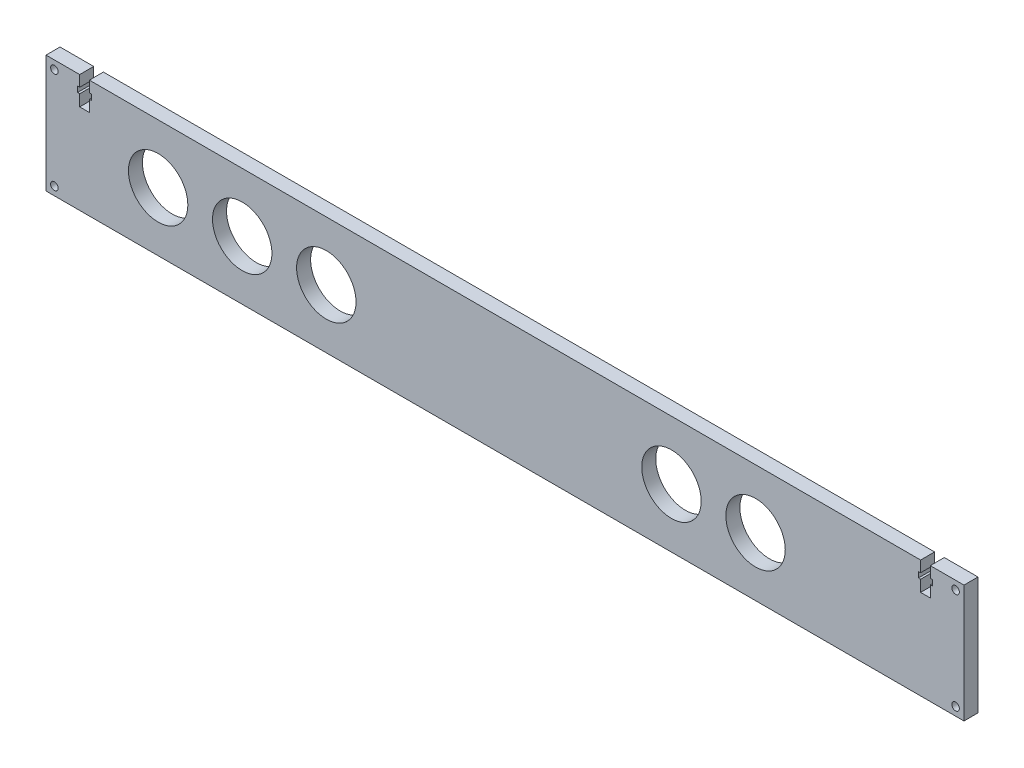
SolidWorks part; units mm, degrees
material "Acrylic (Medium-high impact)"
ref_plane "Front Plane" through (0, 0, 0) normal (0, 0, 1) x (1, 0, 0)
ref_plane "Top Plane" through (0, 0, 0) normal (0, 1, 0) x (1, 0, 0)
ref_plane "Right Plane" through (0, 0, 0) normal (1, 0, 0) x (0, 0, -1)
sketch "Sketch1" plane through (0, 0, 0) normal (0, 0, 1) x (1, 0, 0)
  line L1 (-458.8532, 202.2287) -> (-42.9282, 202.2287)
  line L2 (-458.8532, 202.2287) -> (-458.8532, 148.8887)
  line L3 (-458.8532, 148.8887) -> (-42.9282, 148.8887)
  line L4 (-42.9282, 202.2287) -> (-42.9282, 148.8887)
  line L5 (-458.8532, 202.2287) -> (-42.9282, 148.8887) construction
  line L6 (-458.8532, 148.8887) -> (-42.9282, 202.2287) construction
  point P0 (-250.8907, 175.5587)
  dimension "D1" = 415.925
  dimension "D2" = 53.34
extrude "Boss-Extrude1" add sketch "Sketch1" along normal blind 6.35
sketch "Sketch6" plane through (0, 0, 6.35) normal (0, 0, 1) x (1, 0, 0)
  line L0 (-42.9282, 175.5587) -> (-460.2982, 175.5587) construction
  line L1 (-42.9282, 148.8887) -> (-42.9282, 202.2287) construction
  line L2 (-458.8532, 202.2287) -> (-458.8532, 148.8887) construction
  circle A0 centre (-408.0532, 175.5587) radius 13.462
  circle A1 centre (-175.4677, 175.5587) radius 13.462
  circle A2 centre (-369.9532, 175.5587) radius 13.462
  circle A3 centre (-331.8532, 175.5587) radius 13.462
  circle A4 centre (-137.3677, 175.5587) radius 13.462
  dimension "D1" = 26.924
  dimension "D2" = 50.8
  dimension "D3" = 26.924
  dimension "D4" = 3
  dimension "D5" = 2
extrude "Cut-Extrude4" cut sketch "Sketch6" against normal through all
hole_wizard "#29 (0.136) Diameter Hole1" positions "Sketch7" profile "Sketch8" hole size "#29" standard "ANSI Inch" end condition through all
sketch "Sketch7" plane through (0, 0, 6.35) normal (0, 0, 1) x (1, 0, 0)
  line L12 (-42.9282, 148.8887) -> (-458.8532, 202.2287) construction
  line L13 (-42.9282, 202.2287) -> (-458.8532, 202.2287) construction
  line L15 (-46.7382, 198.4187) -> (-455.0432, 198.4187) construction
  line L16 (-46.7382, 198.4187) -> (-46.7382, 152.6987) construction
  line L17 (-46.7382, 152.6987) -> (-455.0432, 152.6987) construction
  line L18 (-455.0432, 198.4187) -> (-455.0432, 152.6987) construction
  line L19 (-46.7382, 198.4187) -> (-455.0432, 152.6987) construction
  line L20 (-46.7382, 152.6987) -> (-455.0432, 198.4187) construction
  line L21 (-42.9282, 148.8887) -> (-42.9282, 202.2287) construction
  line L22 (-458.8532, 202.2287) -> (-458.8532, 148.8887) construction
  point P110 (-455.0432, 152.6987)
  point P143 (-46.7382, 198.4187)
  point P144 (-46.7382, 152.6987)
  point P145 (-455.0432, 198.4187)
  dimension "D1" = 3.81
  dimension "D2" = 3.81
  dimension "D3" = 3.81
sketch "Sketch8" plane through (-455.0432, 198.4187, 6.35) normal (1, 0, 0) x (0, -1, 0)
  line L0 (0, 0) -> (0, 6.35)
  line L1 (0, 6.35) -> (1.7272, 6.35)
  line L2 (1.7272, 6.35) -> (1.7272, 0)
  line L5 (1.7272, 0) -> (0, 0)
  line L11 (0, -6.35) -> (0, 107.95) construction
  dimension "Thru Hole Dia." = 3.4544
  dimension "Thru Hole Depth" = 6.35
sketch "Sketch5" plane through (0, 0, 0) normal (0, 0, -1) x (-1, 0, 0)
  line L0 (42.9282, 202.2287) -> (458.8532, 202.2287) construction
  line L1 (443.5878, 202.2287) -> (439.1936, 202.2287)
  line L2 (443.5878, 202.2287) -> (443.5878, 197.2281)
  line L3 (443.5878, 189.5287) -> (439.1936, 189.5287)
  line L4 (439.1936, 202.2287) -> (439.1936, 197.2281)
  line L5 (458.8532, 202.2287) -> (458.8532, 148.8887) construction
  line L6 (62.5878, 202.2287) -> (58.1936, 202.2287)
  line L7 (439.1936, 197.2281) -> (438.2157, 197.2281)
  line L8 (444.5657, 197.2281) -> (443.5878, 197.2281)
  line L9 (444.5657, 197.2281) -> (444.5657, 194.6881)
  line L10 (444.5657, 194.6881) -> (443.5878, 194.6881)
  line L11 (438.2157, 197.2281) -> (438.2157, 194.6881)
  line L12 (62.5878, 202.2287) -> (62.5878, 197.2281)
  line L13 (62.5878, 189.5287) -> (58.1936, 189.5287)
  line L14 (58.1936, 202.2287) -> (58.1936, 197.2281)
  line L15 (58.1936, 197.2281) -> (57.2157, 197.2281)
  line L16 (439.1936, 194.6881) -> (438.2157, 194.6881)
  line L17 (443.5878, 194.6881) -> (443.5878, 189.5287)
  line L18 (63.5657, 197.2281) -> (62.5878, 197.2281)
  line L19 (439.1936, 194.6881) -> (439.1936, 189.5287)
  line L20 (63.5657, 197.2281) -> (63.5657, 194.6881)
  line L21 (63.5657, 194.6881) -> (62.5878, 194.6881)
  line L22 (57.2157, 197.2281) -> (57.2157, 194.6881)
  line L23 (58.1936, 194.6881) -> (57.2157, 194.6881)
  line L24 (62.5878, 194.6881) -> (62.5878, 189.5287)
  line L25 (58.1936, 194.6881) -> (58.1936, 189.5287)
  point P8 (439.1936, 195.8787)
  point P22 (58.1936, 195.8787)
  dimension "D1" = 12.7
  dimension "D2" = 4.3942
  dimension "D3" = 15.2654
  dimension "D4" = 2.54
  dimension "D5" = 6.35
  dimension "D6" = 2
extrude "Cut-Extrude3" cut sketch "Sketch5" against normal through all
